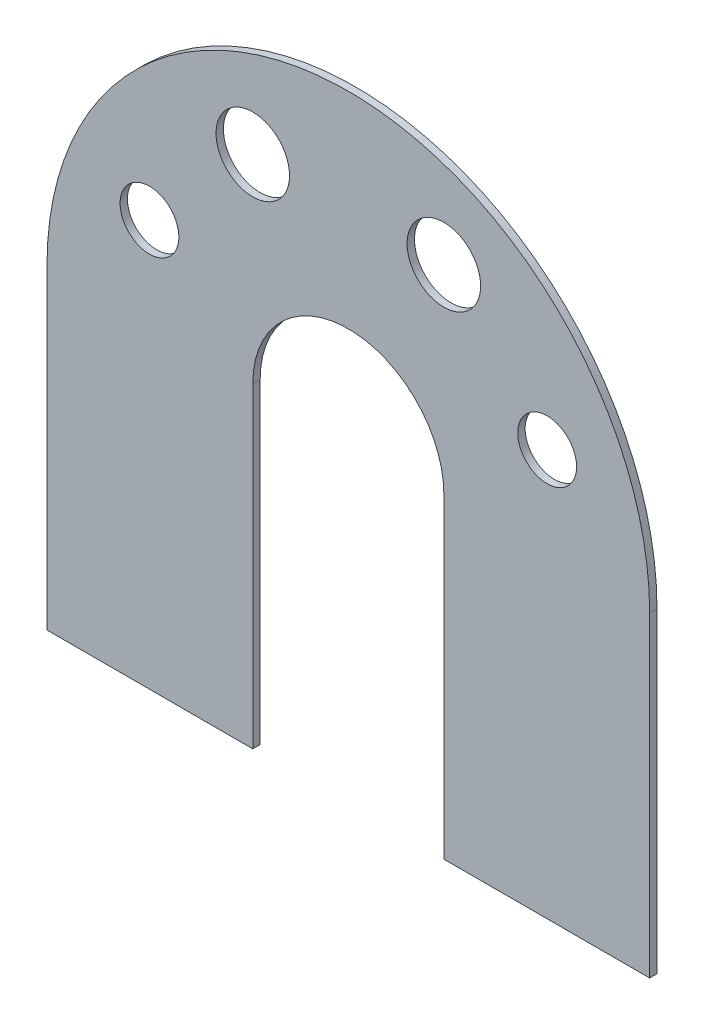
SolidWorks part; units mm, degrees
material "Q235"
ref_plane "前视基准面" through (0, 0, 0) normal (0, 0, 1) x (1, 0, 0)
ref_plane "上视基准面" through (0, 0, 0) normal (0, 1, 0) x (1, 0, 0)
ref_plane "右视基准面" through (0, 0, 0) normal (1, 0, 0) x (0, 0, -1)
sketch "草图1" plane through (0, 0, 0) normal (0, 0, 1) x (1, 0, 0)
  line L1 (-410, 0) -> (-410, -430)
  line L2 (-410, -430) -> (410, -430)
  line L3 (410, -430) -> (410, 0)
  arc A0 (410, 0) -> (-410, 0) centre (0, 0) ccw
  dimension "D1" = 820
  dimension "D2" = 430
extrude "凸台-拉伸1" add sketch "草图1" along normal blind 10
sketch "草图3" plane through (0, 0, 10) normal (0, 0, 1) x (1, 0, 0)
  line L0 (0, 410) -> (0, 0) construction
  line L1 (-130, 0) -> (-130, -430)
  line L2 (-410, -430) -> (410, -430) construction
  line L3 (-130, -430) -> (130, -430)
  line L4 (130, -430) -> (130, 0)
  circle A0 centre (-130, 270.4384) radius 50
  circle A1 centre (130, 270.4384) radius 50
  circle A2 centre (-270.5628, 122.7017) radius 40
  circle A3 centre (270.5628, 122.7017) radius 40
  arc A4 (410, 0) -> (-410, 0) centre (0, 0) ccw construction
  arc A5 (130, 0) -> (-130, 0) centre (0, 0) ccw
  point P17 (-270.5628, 122.7017)
  point P19 (130, 270.4384)
  dimension "D1" = 260
  dimension "D2" = 100
  dimension "D4" = 100
  dimension "D5" = 80
  dimension "D7" = 80
extrude "切除-拉伸3" cut sketch "草图3" against normal blind 50
